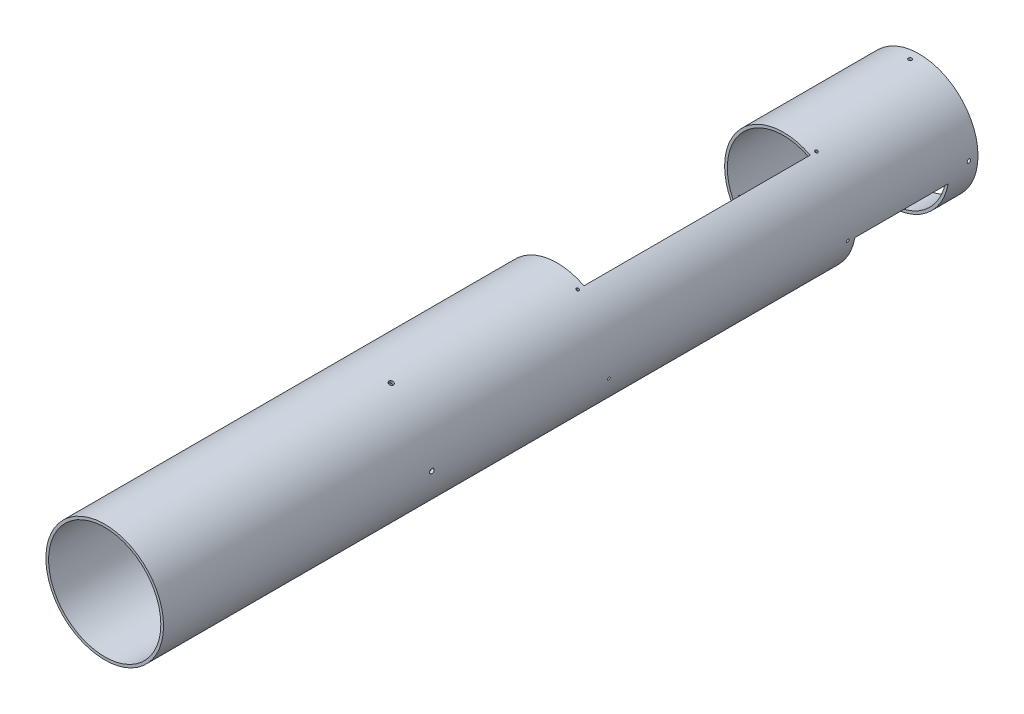
SolidWorks part; units mm, degrees
ref_plane "Front Plane" through (0, 0, 0) normal (0, 0, 1) x (1, 0, 0)
ref_plane "Top Plane" through (0, 0, 0) normal (0, 1, 0) x (1, 0, 0)
ref_plane "Right Plane" through (0, 0, 0) normal (1, 0, 0) x (0, 0, -1)
sketch "Sketch1" plane through (0, 0, 0) normal (0, 0, 1) x (1, 0, 0)
  circle A0 centre (0, 0) radius 62
  circle A1 centre (0, 0) radius 65
  dimension "D1" = 124
  dimension "D2" = 3
extrude "Boss-Extrude1" add sketch "Sketch1" along normal blind 900
sketch "Sketch2" plane through (0, 0, 0) normal (0, 1, 0) x (1, 0, 0)
  line L0 (62, 0) -> (-62, 0) construction
  circle A0 centre (0, -224) radius 1
  circle A1 centre (0, -264) radius 1
  dimension "D1" = 2
  dimension "D3" = 2
  dimension "D2" = 224
  dimension "D4" = 40
ref_plane "Plane1" through (0, 0, 0) normal (-0.7071, 0.7071, 0) x (0.7071, 0.7071, 0)
ref_plane "Plane2" through (-14.1421, 14.1421, 0) normal (-0.7071, 0.7071, 0) x (0.7071, 0.7071, 0)
sketch "Sketch4" plane through (-14.1421, 14.1421, 0) normal (-0.7071, 0.7071, 0) x (0.7071, 0.7071, 0)
  line L0 (-65, 0) -> (-65, -900) construction
  line L1 (-65, -150) -> (65, -150)
  line L2 (-65, -150) -> (-65, -400)
  line L3 (-65, -400) -> (65, -400)
  line L4 (65, -150) -> (65, -400)
  line L5 (65, -900) -> (65, 0) construction
  line L6 (65, 0) -> (-65, 0) construction
  dimension "D1" = 150
  dimension "D2" = 250
extrude "Cut-Extrude4" cut sketch "Sketch4" along normal blind 516
sketch "Sketch5" plane through (0, 0, 0) normal (0, 1, 0) x (1, 0, 0)
  line L0 (-62, 0) -> (62, 0) construction
  circle A0 centre (0, -10) radius 2
  dimension "D1" = 4
  dimension "D2" = 10
extrude "Cut-Extrude5" cut sketch "Sketch5" against normal blind 85
pattern_circular "CirPattern1" count 4 every 90 about axis through (0, 0, 900) along (0, 0, -1) of "Cut-Extrude5"
sketch "Sketch7" plane through (-14.1421, 14.1421, 0) normal (-0.7071, 0.7071, 0) x (0.7071, 0.7071, 0)
  line L0 (-61.8466, -150) -> (61.8466, -150) construction
  line L1 (58.6856, -400) -> (-58.6856, -400) construction
  circle A0 centre (0, -143) radius 1.5
  circle A1 centre (0, -407) radius 1.5
  dimension "D1" = 3
  dimension "D3" = 3
  dimension "D2" = 7
  dimension "D4" = 7
extrude "Cut-Extrude6" cut sketch "Sketch7" along normal blind 243
pattern_circular "CirPattern2" count 5 every 72 about axis through (0, 0, 900) along (0, 0, -1) of "Cut-Extrude6"
sketch "Sketch8" plane through (0, 0, 0) normal (1, 0, 0) x (0, 0, -1)
  line L0 (-900, 65) -> (-900, -65) construction
  circle A0 centre (-603.5, 0) radius 2.5
  dimension "D2" = 5
  dimension "D1" = 296.5
extrude "Cut-Extrude7" cut sketch "Sketch8" along normal blind 209
pattern_circular "CirPattern3" count 5 every 72 about axis through (0, 0, 900) along (0, 0, -1) of "Cut-Extrude7"
ref_plane "Plane3" through (0, 0, 135) normal (0, 0, 1) x (1, 0, 0)
sketch "Sketch9" plane through (0, 0, 135) normal (0, 0, 1) x (1, 0, 0)
  line L0 (-72.0694, 72.0694) -> (72.0694, -72.0694) construction
  line L2 (38.8909, 38.8909) -> (-38.8909, -38.8909) construction
  line L3 (0, 0) -> (11.2871, -64.0125)
  line L4 (1, 0) -> (-1, 0) construction
  line L5 (0, 0) -> (64.0125, -11.2871)
  arc A0 (11.2871, -64.0125) -> (64.0125, -11.2871) centre (0, 0) ccw
  point P6 (0, 0)
  dimension "D1" = 35
extrude "Cut-Extrude8" cut sketch "Sketch9" against normal blind 103
ref_plane "Plane4" through (-14.1421, 14.1421, 0) normal (-0.7071, 0.7071, 0) x (0.7071, 0.7071, 0)
sketch "Sketch11" plane through (-14.1421, 14.1421, 0) normal (-0.7071, 0.7071, 0) x (0.7071, 0.7071, 0)
  line L0 (0, 0) -> (1.5, -407) construction
  circle A0 centre (0, -407) radius 1.5 construction
ref_plane "Plane5" through (0, 0, 0) normal (-0.7071, -0.7071, 0.0037) x (0.0026, 0.0026, 1)
sketch "Sketch12" plane through (0, 0, 0) normal (-0.7071, -0.7071, 0.0037) x (0.0026, 0.0026, 1)
  line L0 (149.999, 65) -> (399.9973, 65) construction
  line L1 (274.9981, 65) -> (274.9981, 0)
  line L3 (274.9981, 149.9397) -> (274.9981, 40.3241) construction
  spline S0 degree 3 poles (187.3778, -3.3501) (176.2942, 24.6761) (155.0428, 1.5015) (169.898, -11.7468) (187.3778, -3.3501) (176.2942, 24.6761) (155.0428, 1.5015) knots -0.687115 -0.495852 -0.289433 0 0.312885 0.504148 0.710567 1 1.312885 1.504148 1.710567 only from (174.7972, 14.9821) to (174.7972, 14.9821)
  spline S1 degree 1 poles (174.7972, 14.9821) (274.9981, 175.3798) knots 0 0 1 1
  spline S2 degree 3 poles (362.6185, -3.3501) (373.702, 24.6761) (394.9535, 1.5015) (380.0983, -11.7468) (362.6185, -3.3501) (373.702, 24.6761) (394.9535, 1.5015) knots -0.687115 -0.495852 -0.289433 0 0.312885 0.504148 0.710567 1 1.312885 1.504148 1.710567 only from (375.199, 14.9821) to (375.199, 14.9821)
  spline S3 degree 1 poles (375.199, 14.9821) (274.9981, 175.3798) knots 0 0 1 1
  point P11 (274.9981, 0)
  dimension "D1" = 65
  dimension "D2" = 100.2009
  dimension "D3" = 0
  dimension "D4" = 100.2009
ref_plane "Plane6" through (-123.2956, 124.7289, 274.9963) normal (0.7071, -0.7071, 0) x (-0.7071, -0.7071, 0)
sketch "Sketch15" plane through (-123.2956, 124.7289, 274.9963) normal (0.7071, -0.7071, 0) x (-0.7071, -0.7071, 0)
  circle A0 centre (0, 0) radius 1.5
sketch "Sketch16" plane through (-124.0123, 124.0123, -175.3798) normal (0.7071, -0.7071, 0) x (0.5, 0.5, -0.7071)
  circle A0 centre (0, 0) radius 1.5
ref_plane "Plane7" through (0, 0, 275) normal (0, 0, -1) x (-1, 0, 0)
